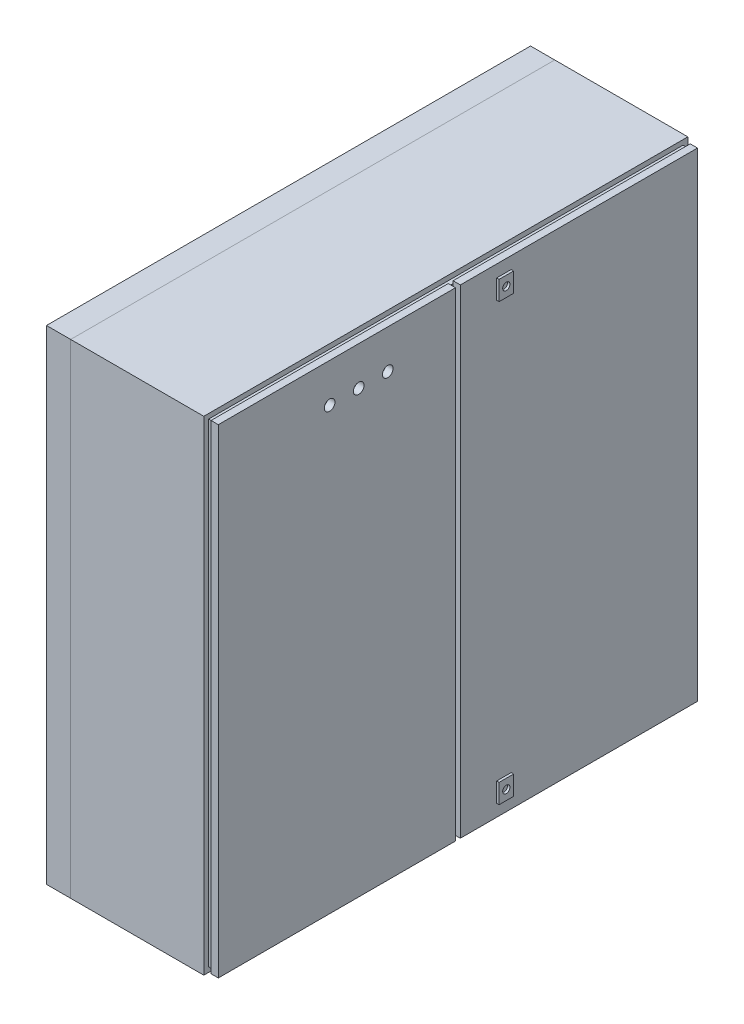
SolidWorks part; units mm, degrees
ref_plane "Front Plane" through (0, 0, 0) normal (0, 0, 1) x (1, 0, 0)
ref_plane "Top Plane" through (0, 0, 0) normal (0, 1, 0) x (1, 0, 0)
ref_plane "Right Plane" through (0, 0, 0) normal (1, 0, 0) x (0, 0, -1)
sketch "Sketch1" plane through (0, 0, 0) normal (1, 0, 0) x (0, 0, -1)
  line L1 (-500, -500) -> (500, -500)
  line L2 (-500, -500) -> (-500, 500)
  line L3 (-500, 500) -> (500, 500)
  line L4 (500, -500) -> (500, 500)
  line L5 (-500, -500) -> (500, 500) construction
  line L6 (-500, 500) -> (500, -500) construction
  point P0 (0, 0)
  dimension "D1" = 1000
extrude "Boss-Extrude1" add sketch "Sketch1" along normal blind 275
sketch "Sketch2" plane through (275, 0, 0) normal (1, 0, 0) x (0, 0, -1)
  line L0 (-5, 495) -> (-5, -495)
  line L1 (-495, -495) -> (495, -495) construction
  line L2 (-495, -495) -> (-495, 495)
  line L3 (-495, 495) -> (495, 495) construction
  line L4 (495, -495) -> (495, 495)
  line L5 (-495, -495) -> (495, 495) construction
  line L6 (-495, 495) -> (495, -495) construction
  line L7 (0, 0) -> (0, 145.4338) construction
  line L8 (5, 495) -> (5, -495)
  line L9 (-495, 495) -> (-5, 495)
  line L10 (5, 495) -> (495, 495)
  line L11 (495, -495) -> (5, -495)
  line L12 (-5, -495) -> (-495, -495)
  point P0 (0, 0)
  dimension "D1" = 990
  dimension "D2" = 490
extrude "Boss-Extrude2" add sketch "Sketch2" along normal blind 15 from offset 10 separate body
sketch "Sketch3" plane through (275, 0, 0) normal (1, 0, 0) x (0, 0, -1)
  line L4 (500, -500) -> (500, 500)
  line L5 (500, 500) -> (-500, 500)
  line L6 (-500, 500) -> (-500, -500)
  line L7 (-500, -500) -> (500, -500)
  line L8 (500, -500) -> (500, 500) construction
  line L9 (500, 500) -> (-500, 500) construction
  line L10 (-500, 500) -> (-500, -500) construction
  line L11 (-500, -500) -> (500, -500) construction
  line L12 (480, 480) -> (-480, 480)
  line L13 (-480, 480) -> (-480, -480)
  line L14 (-480, -480) -> (480, -480)
  line L15 (480, -480) -> (480, 480)
  line L16 (490, -490) -> (490, 490)
  line L17 (490, 490) -> (-490, 490)
  line L18 (-490, 490) -> (-490, -490)
  line L19 (-490, -490) -> (490, -490)
  line L20 (490, -490) -> (490, 490)
  line L21 (490, 490) -> (-490, 490)
  line L22 (-490, 490) -> (-490, -490)
  line L23 (-490, -490) -> (490, -490)
  dimension "D1" = 0
  dimension "D2" = 10
  dimension "D3" = 10
extrude "Boss-Extrude3" add sketch "Sketch3" along normal blind 10
sketch "Sketch4" plane through (0, 0, 0) normal (-1, 0, 0) x (0, 0, 1)
  line L0 (-450, 450) -> (-450, -450)
  line L1 (-450, -450) -> (450, -450)
  line L2 (450, -450) -> (450, 450)
  line L3 (450, 450) -> (-450, 450)
  line L4 (-500, 500) -> (-500, -500)
  line L5 (-500, -500) -> (500, -500)
  line L6 (500, -500) -> (500, 500)
  line L7 (500, 500) -> (-500, 500)
  line L8 (-500, 500) -> (-500, -500)
  line L9 (-500, -500) -> (500, -500)
  line L10 (500, -500) -> (500, 500)
  line L11 (500, 500) -> (-500, 500)
  dimension "D1" = 0
  dimension "D2" = 50
extrude "Boss-Extrude4" add sketch "Sketch4" along normal blind 50 separate body
sketch "Sketch5" plane through (300, 0, 0) normal (1, 0, 0) x (0, 0, -1)
  line L0 (-495, 495) -> (-495, -495) construction
  line L1 (-5, 495) -> (-495, 495) construction
  circle A0 centre (-265, 415) radius 11
  circle A1 centre (-205, 415) radius 11
  circle A2 centre (-145, 415) radius 11
  dimension "D1" = 22
  dimension "D2" = 230
  dimension "D3" = 80
  dimension "D5" = 60
  dimension "D4" = 3
extrude "Cut-Extrude1" cut sketch "Sketch5" against normal blind 25
sketch "Sketch6" plane through (300, 0, 0) normal (1, 0, 0) x (0, 0, -1)
  line L0 (0, 0) -> (430.2229, 0) construction
  line L1 (80, 430) -> (110, 430)
  line L2 (80, 430) -> (80, 470)
  line L3 (80, 470) -> (110, 470)
  line L4 (110, 430) -> (110, 470)
  line L5 (80, 430) -> (110, 470) construction
  line L6 (80, 470) -> (110, 430) construction
  line L7 (80, -430) -> (110, -430)
  line L8 (110, -430) -> (110, -470)
  line L9 (80, -430) -> (80, -470)
  line L10 (80, -470) -> (110, -470)
  line L11 (500, 500) -> (-500, 500) construction
  line L12 (5, 495) -> (5, -495) construction
  circle A0 centre (95, 450) radius 7.5
  circle A1 centre (95, -450) radius 7.5
  point P0 (95, 450)
  dimension "D5" = 15
  dimension "D1" = 30
  dimension "D2" = 40
  dimension "D3" = 70
  dimension "D4" = 105
extrude "Boss-Extrude5" add sketch "Sketch6" along normal blind 5 separate body
